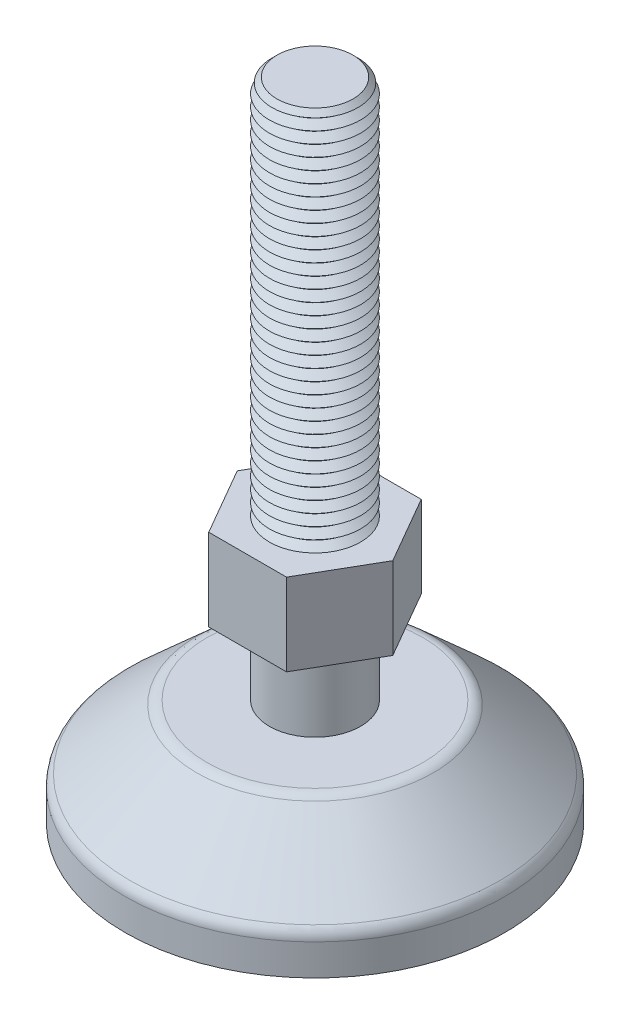
SolidWorks part; units mm, degrees
ref_plane "前视基准面" through (0, 0, 0) normal (0, 0, 1) x (1, 0, 0)
ref_plane "上视基准面" through (0, 0, 0) normal (0, 1, 0) x (1, 0, 0)
ref_plane "右视基准面" through (0, 0, 0) normal (1, 0, 0) x (0, 0, -1)
sketch "草图4" plane through (0, 0, 0) normal (0, 0, 1) x (1, 0, 0)
  line B0 (0, 85) -> (0, 0)
  line B1 (25, 0) -> (0, 0)
  line B2 (25, 0) -> (25, 4.1093)
  line B3 (6, 35) -> (10.235, 35)
  line B4 (6, 14) -> (6, 24.2)
  line B5 (14.2325, 14) -> (6, 14)
  line B6 (24.3379, 5.5959) -> (15.5705, 13.4866)
  line B7 (10.235, 35) -> (10.235, 24.2)
  line B8 (6, 24.2) -> (10.235, 24.2)
  line B9 (5, 85) -> (0, 85)
  line B10 (5, 85) -> (5.6558, 84.3442)
  line B11 (6, 35) -> (5, 35.7516)
  line B12 (6, 36.5031) -> (5, 35.7516)
  line B13 (6, 36.5031) -> (5, 37.2547)
  line B14 (6, 38.0062) -> (5, 37.2547)
  line B15 (6, 38.0062) -> (5, 38.7578)
  line B16 (6, 39.5093) -> (5, 38.7578)
  line B17 (6, 39.5093) -> (5, 40.2609)
  line B18 (6, 41.0125) -> (5, 40.2609)
  line B19 (6, 41.0125) -> (5, 41.764)
  line B20 (6, 42.5156) -> (5, 41.764)
  line B21 (6, 42.5156) -> (5, 43.2671)
  line B22 (6, 44.0187) -> (5, 43.2671)
  line B23 (6, 44.0187) -> (5, 44.7703)
  line B24 (6, 45.5218) -> (5, 44.7703)
  line B25 (6, 45.5218) -> (5, 46.2734)
  line B26 (6, 47.0249) -> (5, 46.2734)
  line B27 (6, 47.0249) -> (5, 47.7765)
  line B28 (6, 48.528) -> (5, 47.7765)
  line B29 (6, 48.528) -> (5, 49.2796)
  line B30 (6, 50.0312) -> (5, 49.2796)
  line B31 (6, 50.0312) -> (5, 50.7827)
  line B32 (6, 51.5343) -> (5, 50.7827)
  line B33 (6, 51.5343) -> (5, 52.2858)
  line B34 (6, 53.0374) -> (5, 52.2858)
  line B35 (6, 53.0374) -> (5, 53.789)
  line B36 (6, 54.5405) -> (5, 53.789)
  line B37 (6, 54.5405) -> (5, 55.2921)
  line B38 (6, 56.0436) -> (5, 55.2921)
  line B39 (6, 56.0436) -> (5, 56.7952)
  line B40 (6, 57.5467) -> (5, 56.7952)
  line B41 (6, 57.5467) -> (5, 58.2983)
  line B42 (6, 59.0499) -> (5, 58.2983)
  line B43 (6, 59.0499) -> (5, 59.8014)
  line B44 (6, 60.553) -> (5, 59.8014)
  line B45 (6, 60.553) -> (5, 61.3045)
  line B46 (6, 62.0561) -> (5, 61.3045)
  line B47 (6, 62.0561) -> (5, 62.8077)
  line B48 (6, 63.5592) -> (5, 62.8077)
  line B49 (6, 63.5592) -> (5, 64.3108)
  line B50 (6, 65.0623) -> (5, 64.3108)
  line B51 (6, 65.0623) -> (5, 65.8139)
  line B52 (6, 66.5654) -> (5, 65.8139)
  line B53 (6, 66.5654) -> (5, 67.317)
  line B54 (6, 68.0686) -> (5, 67.317)
  line B55 (6, 68.0686) -> (5, 68.8201)
  line B56 (6, 69.5717) -> (5, 68.8201)
  line B57 (6, 69.5717) -> (5, 70.3232)
  line B58 (6, 71.0748) -> (5, 70.3232)
  line B59 (6, 71.0748) -> (5, 71.8263)
  line B60 (6, 72.5779) -> (5, 71.8263)
  line B61 (6, 72.5779) -> (5, 73.3295)
  line B62 (6, 74.081) -> (5, 73.3295)
  line B63 (6, 74.081) -> (5, 74.8326)
  line B64 (6, 75.5841) -> (5, 74.8326)
  line B65 (6, 75.5841) -> (5, 76.3357)
  line B66 (6, 77.0873) -> (5, 76.3357)
  line B67 (6, 77.0873) -> (5, 77.8388)
  line B68 (6, 78.5904) -> (5, 77.8388)
  line B69 (6, 78.5904) -> (5, 79.3419)
  line B70 (6, 80.0935) -> (5, 79.3419)
  line B71 (6, 80.0935) -> (5, 80.845)
  line B72 (6, 81.5966) -> (5, 80.845)
  line B73 (6, 81.5966) -> (5, 82.3482)
  line B74 (6, 83.0997) -> (5, 82.3482)
  line B75 (6, 83.0997) -> (5, 83.8513)
  line B76 (5.6558, 84.3442) -> (5, 83.8513)
  arc B77 (15.5705, 13.4866) -> (14.2325, 14) centre (14.2325, 12) ccw
  arc B78 (25, 4.1093) -> (24.3379, 5.5959) centre (23, 4.1093) ccw
sketch_block_instance "A$C62D51F77-1"
sketch_block "A$C62D51F77"
revolve "旋转2" add sketch "草图4" angle 360 about L0
sketch "草图6" plane through (0, 35, 0) normal (0, 1, 0) x (1, 0, 0)
  line L1 (10.235, 0) -> (5.1175, 8.8638)
  line L2 (5.1175, 8.8638) -> (-5.1175, 8.8638)
  line L3 (-5.1175, 8.8638) -> (-10.235, 0)
  line L4 (-10.235, 0) -> (-5.1175, -8.8638)
  line L5 (-5.1175, -8.8638) -> (5.1175, -8.8638)
  line L6 (5.1175, -8.8638) -> (10.235, 0)
  circle A0 centre (0, 0) radius 14.593
extrude "切除-拉伸2" cut sketch "草图6" against normal blind 12
